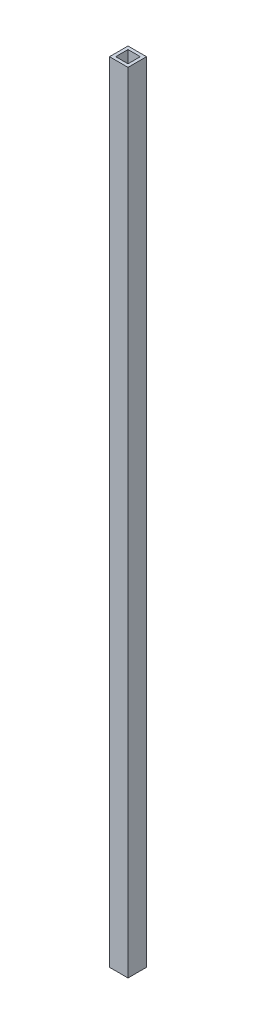
SolidWorks part; units mm, degrees
ref_plane "Front Plane" through (0, 0, 0) normal (0, 0, 1) x (1, 0, 0)
ref_plane "Top Plane" through (0, 0, 0) normal (0, 1, 0) x (1, 0, 0)
ref_plane "Right Plane" through (0, 0, 0) normal (1, 0, 0) x (0, 0, -1)
sketch "Sketch1" plane through (0, 0, 0) normal (0, 1, 0) x (1, 0, 0)
  line L1 (0, 0) -> (19.05, 0)
  line L2 (0, 0) -> (0, 19.05)
  line L3 (0, 19.05) -> (19.05, 19.05)
  line L4 (19.05, 0) -> (19.05, 19.05)
  dimension "D1" = 19.05
  dimension "D2" = 19.05
extrude "Extrude-Thin1" add sketch "Sketch1" along normal blind 812.8 thin thin type one direction reverse wall 3.175
